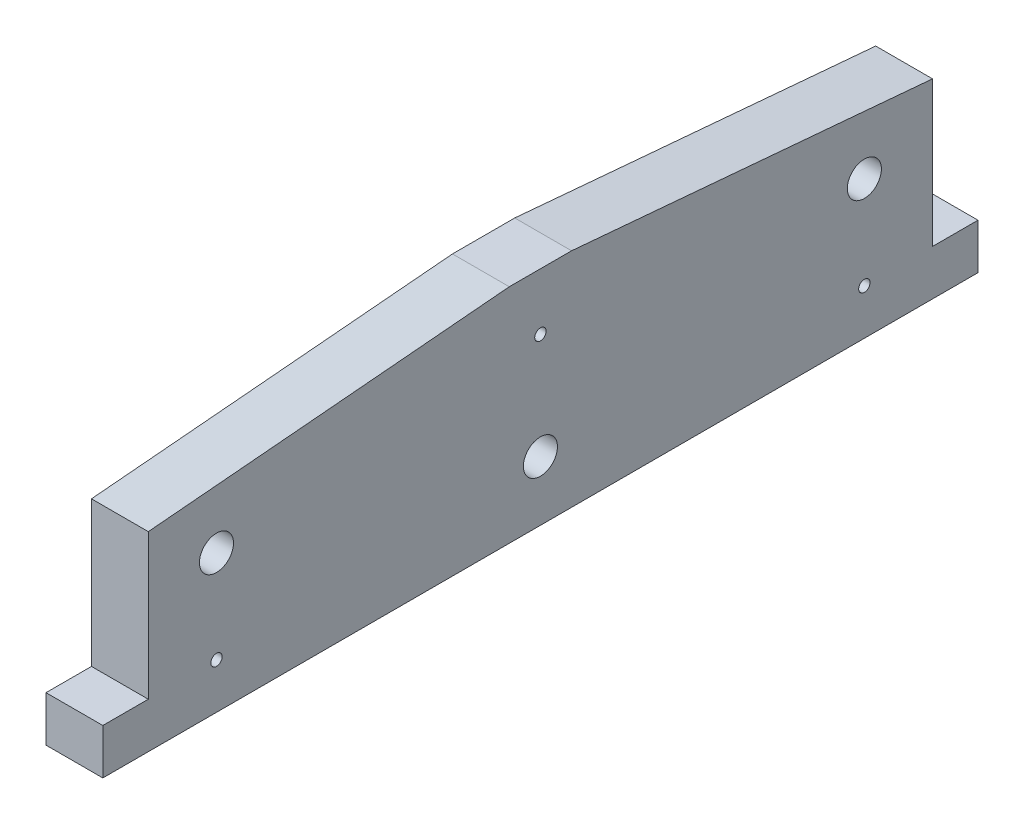
SolidWorks part; units mm, degrees
ref_plane "Plano frontal" through (0, 0, 0) normal (0, 0, 1) x (1, 0, 0)
ref_plane "Plano superior" through (0, 0, 0) normal (0, 1, 0) x (1, 0, 0)
ref_plane "Plano direito" through (0, 0, 0) normal (1, 0, 0) x (0, 0, -1)
sketch "Esboço2" plane through (0, 0, 0) normal (1, 0, 0) x (0, 0, -1)
  line L1 (69.5, -29.4899) -> (77.5, -29.4899)
  line L2 (77.5, -37.4899) -> (77.5, -29.4899)
  line L4 (77.5, -37.4899) -> (-76.5, -37.4899)
  line L7 (-76.5, -37.4899) -> (-76.5, -29.4899)
  line L9 (-76.5, -29.4899) -> (-68.5, -29.4899)
  line L13 (-68.5, -3.948) -> (-68.5, -29.4899)
  line L14 (-4.9782, 1.6094) -> (-68.5, -3.948)
  line L15 (-4.9782, 1.6094) -> (0, 1.6094)
  line L16 (5.9782, 1.6094) -> (0, 1.6094)
  line L17 (5.9782, 1.6094) -> (69.5, -3.948)
  line L18 (69.5, -3.948) -> (69.5, -29.4899)
  dimension "D1" = 138
  dimension "D2" = 8
  dimension "D3" = 8
  dimension "D5" = 8
  dimension "D6" = 31.0993
  dimension "D4" = 8
extrude "Ressalto-extrusão2" add sketch "Esboço2" along normal blind 10
sketch "Sketch1" plane through (0, 0, 0) normal (-1, 0, 0) x (0, 0, 1)
  line L0 (-0.5, 1.6094) -> (-0.5, -37.4899) construction
  line L4 (76.5, -37.4899) -> (-77.5, -37.4899) construction
  line L6 (-5.9782, 1.6094) -> (4.9782, 1.6094) construction
sketch "Esboço3" plane through (10, 0, 0) normal (1, 0, 0) x (0, 0, -1)
  circle A0 centre (0.5, -8.3906) radius 1
  circle A1 centre (0.5, -27.0028) radius 3
  circle A2 centre (57.5, -13.1788) radius 3
  circle A3 centre (57.5, -29.4899) radius 1
  circle A4 centre (-56.5, -13.1788) radius 3
  circle A5 centre (-56.5, -29.4899) radius 1
extrude "Corte-extrusão1" cut sketch "Esboço3" against normal through all
